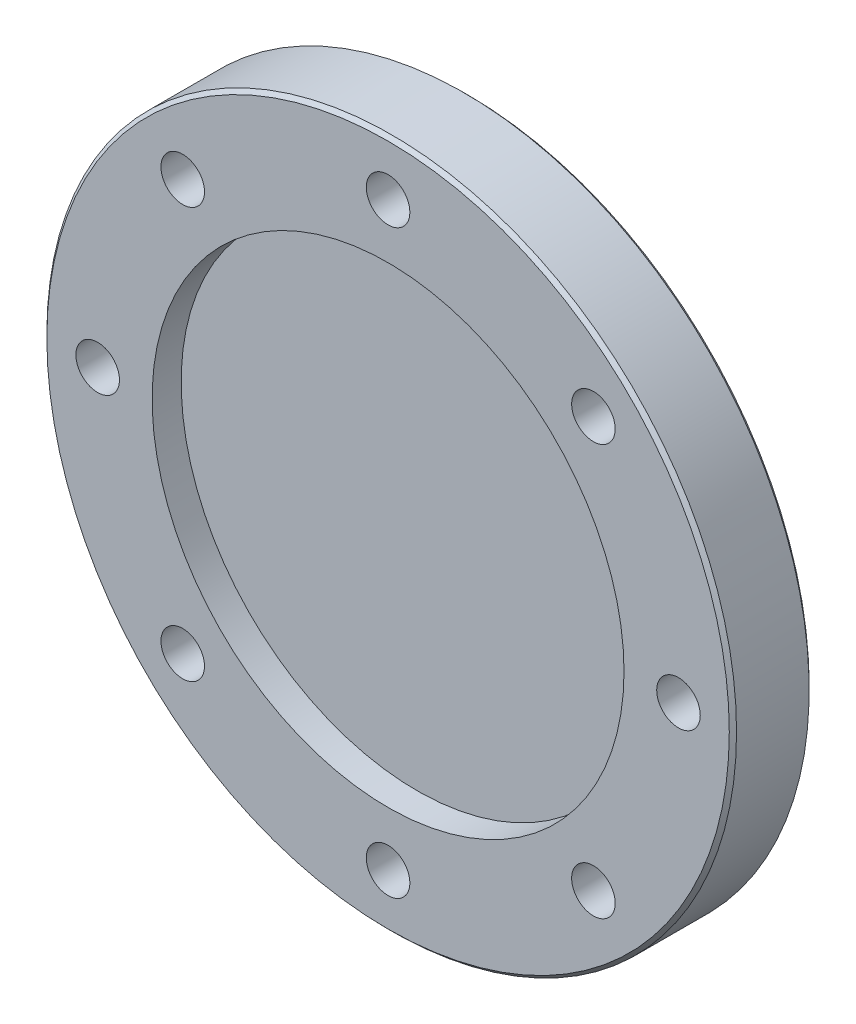
SolidWorks part; units mm, degrees
ref_plane "前视基准面" through (0, 0, 0) normal (0, 0, 1) x (1, 0, 0)
ref_plane "上视基准面" through (0, 0, 0) normal (0, 1, 0) x (1, 0, 0)
ref_plane "右视基准面" through (0, 0, 0) normal (1, 0, 0) x (0, 0, -1)
other "Configuration Table"
sketch "草图1" plane through (0, 0, 0) normal (1, 0, 0) x (0, 0, -1)
  line L0 (0, 0) -> (0, 47.5)
  line L1 (0, 47.5) -> (11, 47.5)
  line L2 (11, 47.5) -> (11, 19)
  line L3 (11, 19) -> (12, 19)
  line L4 (12, 19) -> (12, 15)
  line L5 (12, 15) -> (31, 15)
  line L6 (31, 15) -> (31, 0)
  line L7 (31, 0) -> (0, 0)
  line L8 (0, 0) -> (-18.7863, 0) construction
  dimension "D1" = 95
  dimension "D2" = 38
  dimension "D3" = 30
  dimension "D4" = 11
  dimension "D5" = 12
  dimension "D6" = 31
revolve "旋转1" add sketch "草图1" angle 360 about L8
sketch "草图3" plane through (0, 0, 0) normal (0, 0, 1) x (1, 0, 0)
  circle A0 centre (0, 0) radius 32.5
  dimension "D1" = 65
extrude "切除-拉伸1" cut sketch "草图3" against normal blind 4
hole_wizard "大小mm 暗销孔1" positions "草图4" profile "草图5" hole size "Ø8.0" standard "GB"
sketch "草图4" plane through (0, 0, -31) normal (0, 0, -1) x (-1, 0, 0)
  point P0 (0, 0)
sketch "草图5" plane through (0, 0, -31) normal (1, 0, 0) x (0, 1, 0)
  line L0 (0, 0) -> (0, 17.4034)
  line L1 (0, 17.4034) -> (4, 15)
  line L2 (4, 15) -> (4, 0)
  line L5 (4, 0) -> (0, 0)
  line L10 (0, 17.4034) -> (-4, 15) construction
  line L11 (0, -6.35) -> (0, 107.95) construction
  dimension "孔直径" = 8
  dimension "孔深度" = 15
  dimension "导头角度" = 118
sketch "草图6" plane through (0, 0, -11) normal (0, 0, -1) x (-1, 0, 0)
  circle A0 centre (0, 0) radius 40 construction
  circle A1 centre (0, 40) radius 3
  circle A2 centre (28.2843, 28.2843) radius 3
  circle A3 centre (40, 0) radius 3
  circle A4 centre (28.2843, -28.2843) radius 3
  circle A5 centre (0, -40) radius 3
  circle A6 centre (-28.2843, -28.2843) radius 3
  circle A7 centre (-40, 0) radius 3
  circle A8 centre (-28.2843, 28.2843) radius 3
  point P5 (0, 0)
  point P6 (40, 0)
  point P22 (0, 0)
  dimension "D1" = 80
  dimension "D2" = 6
  dimension "D3" = 8
extrude "切除-拉伸2" cut sketch "草图6" against normal up to next
chamfer "倒角1" distance 0.5 angle 45 4 edges at (-4, 0, -31) (-15, 0, -31) (-47.5, 0, -11) (-47.5, 0, 0)
